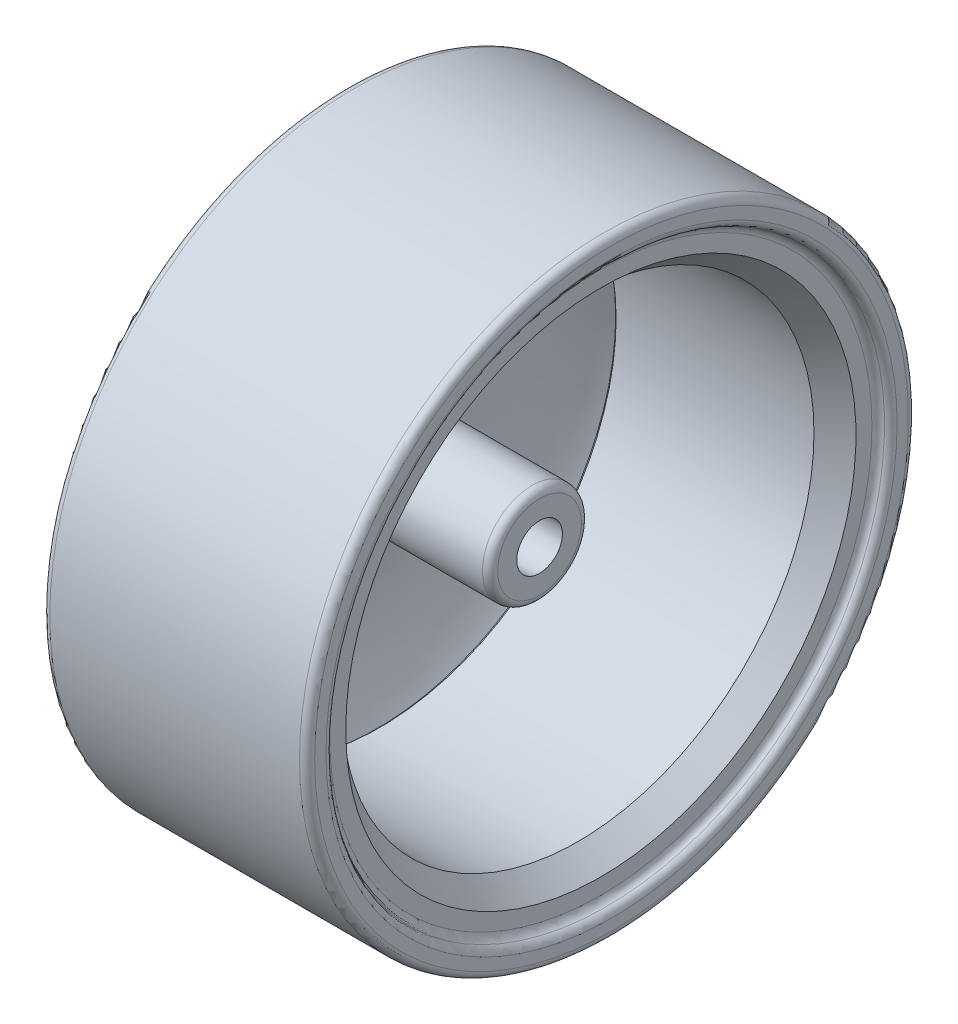
SolidWorks part; units mm, degrees
ref_plane "Front Plane" through (0, 0, 0) normal (0, 0, 1) x (1, 0, 0)
ref_plane "Top Plane" through (0, 0, 0) normal (0, 1, 0) x (1, 0, 0)
ref_plane "Right Plane" through (0, 0, 0) normal (1, 0, 0) x (0, 0, -1)
sketch "Sketch1" plane through (0, 0, 0) normal (0, 1, 0) x (1, 0, 0)
  line L0 (-5, 0) -> (5, 0) construction
  line L1 (0, 0) -> (0, 15.5) construction
  line L2 (6.5, 15.5) -> (-6.5, 15.5)
  line L3 (-6.5, 15.5) -> (-8, 16.7586)
  line L4 (-8, 16.7586) -> (-8, 18.2586)
  line L5 (-8, 18.2586) -> (-6.5, 18.2586)
  line L6 (-6.5, 18.2586) -> (-5, 16.5)
  line L7 (-5, 16.5) -> (5, 16.5)
  line L9 (6.5, 18.2586) -> (5, 16.5)
  line L10 (6.5, 15.5) -> (8, 16.7586)
  line L11 (8, 16.7586) -> (8, 18.2586)
  line L12 (8, 18.2586) -> (6.5, 18.2586)
  point P9 (0, 0)
  dimension "D1" = 6.5
  dimension "D2" = 140
  dimension "D3" = 10
  dimension "D4" = 3
  dimension "D5" = 1.5
  dimension "D6" = 1
  dimension "D7" = 15.5
revolve "Revolve1" add sketch "Sketch1" angle 360 about L0
sketch "Sketch4" plane through (0, 0, 0) normal (0, 1, 0) x (1, 0, 0)
  line L0 (-3.9721, 2.5) -> (3.9721, 2.5) construction
  line L1 (3.9721, 2.5) -> (3.9721, 3.25)
  line L2 (3.9721, 3.25) -> (-7.2779, 3.25)
  line L3 (-8.0279, 2.5) -> (-8.0279, 4.3511)
  line L4 (-8.0279, 2.5) -> (-6.5279, 2.5)
  line L5 (-6.5279, 2.5) -> (-6.5279, 0)
  line L6 (-6.5279, 0) -> (-5.7779, 0)
  line L7 (-5.7779, 0) -> (-5.7779, 2.5)
  line L8 (-5.7779, 2.5) -> (3.9721, 2.5)
  line L9 (-5, 0) -> (5, 0) construction
  line L10 (-7.2779, 3.25) -> (-7.2779, 4.3511)
  line L11 (-7.2411, 16.1218) -> (-6.6665, 15.6397)
  line L12 (-6.5, 15.5) -> (-8, 16.7586) construction
  arc A0 (-8.0279, 4.3511) -> (-7.2411, 16.1218) centre (5.5704, 9.3537) cw
  arc A1 (-7.2779, 4.3511) -> (-6.6665, 15.6397) centre (4.1456, 9.3933) cw
  point P2 (0, 2.5)
  dimension "D9" = 0.75
  dimension "D1" = 0.75
  dimension "D2" = 11.25
  dimension "D3" = 12
  dimension "D4" = 1.5
  dimension "D5" = 0.75
  dimension "D6" = 2.5
  dimension "D7" = 2.5
  dimension "D8" = 0.75
revolve "Revolve2" add sketch "Sketch4" angle 360 about L0
sketch "Sketch5" plane through (0, 0, 0) normal (1, 0, 0) x (0, 0, -1)
  line L0 (0, 0) -> (0, 15.1416) construction
  line L1 (6.3108, 13.7638) -> (1.5, 9.727)
  line L2 (-6.3108, 13.7638) -> (-1.5, 9.727)
  line L3 (15.0403, -1.7487) -> (9.7145, 1.5792)
  line L4 (11.14, 10.2552) -> (8.7874, 4.4324)
  line L5 (2.9846, -14.8446) -> (4.5039, -8.751)
  line L6 (13.1957, -7.4257) -> (6.9309, -6.9877)
  line L7 (-13.1957, -7.4257) -> (-6.9309, -6.9877)
  line L8 (-2.9846, -14.8446) -> (-4.5039, -8.751)
  line L9 (-11.14, 10.2552) -> (-8.7874, 4.4324)
  line L10 (-15.0403, -1.7487) -> (-9.7145, 1.5792)
  arc A0 (-13.1957, -7.4257) -> (-2.9846, -14.8446) centre (0, 0) ccw
  arc A1 (1.5, 9.727) -> (-1.5, 9.727) centre (0, 0) ccw
  arc A2 (9.7145, 1.5792) -> (8.7874, 4.4324) centre (0, 0) ccw
  arc A3 (-11.14, 10.2552) -> (-15.0403, -1.7487) centre (0, 0) ccw
  arc A4 (4.5039, -8.751) -> (6.9309, -6.9877) centre (0, 0) ccw
  arc A5 (-11.14, 10.2552) -> (-15.0403, -1.7487) centre (0, 0) ccw
  arc A6 (-6.9309, -6.9877) -> (-4.5039, -8.751) centre (0, 0) ccw
  arc A7 (-11.14, 10.2552) -> (-15.0403, -1.7487) centre (0, 0) ccw
  arc A8 (-8.7874, 4.4324) -> (-9.7145, 1.5792) centre (0, 0) ccw
  arc A9 (-11.14, 10.2552) -> (-15.0403, -1.7487) centre (0, 0) ccw
  arc A10 (-13.1957, -7.4257) -> (-2.9846, -14.8446) centre (0, 0) ccw
  arc A11 (-13.1957, -7.4257) -> (-2.9846, -14.8446) centre (0, 0) ccw
  arc A12 (-13.1957, -7.4257) -> (-2.9846, -14.8446) centre (0, 0) ccw
  arc A13 (-13.1957, -7.4257) -> (-2.9846, -14.8446) centre (0, 0) ccw
  arc A14 (2.9846, -14.8446) -> (13.1957, -7.4257) centre (0, 0) ccw
  arc A15 (2.9846, -14.8446) -> (13.1957, -7.4257) centre (0, 0) ccw
  arc A16 (2.9846, -14.8446) -> (13.1957, -7.4257) centre (0, 0) ccw
  arc A17 (2.9846, -14.8446) -> (13.1957, -7.4257) centre (0, 0) ccw
  arc A18 (2.9846, -14.8446) -> (13.1957, -7.4257) centre (0, 0) ccw
  arc A19 (15.0403, -1.7487) -> (11.14, 10.2552) centre (0, 0) ccw
  arc A20 (15.0403, -1.7487) -> (11.14, 10.2552) centre (0, 0) ccw
  arc A21 (15.0403, -1.7487) -> (11.14, 10.2552) centre (0, 0) ccw
  arc A22 (15.0403, -1.7487) -> (11.14, 10.2552) centre (0, 0) ccw
  arc A23 (15.0403, -1.7487) -> (11.14, 10.2552) centre (0, 0) ccw
  arc A24 (6.3108, 13.7638) -> (-6.3108, 13.7638) centre (0, 0) ccw
  arc A25 (6.3108, 13.7638) -> (-6.3108, 13.7638) centre (0, 0) ccw
  arc A26 (6.3108, 13.7638) -> (-6.3108, 13.7638) centre (0, 0) ccw
  arc A27 (6.3108, 13.7638) -> (-6.3108, 13.7638) centre (0, 0) ccw
  arc A28 (6.3108, 13.7638) -> (-6.3108, 13.7638) centre (0, 0) ccw
  point P30 (0, 0)
  dimension "D1" = 50
  dimension "D2" = 3
  dimension "D3" = 5
sketch "Sketch6" plane through (0, 0, 0) normal (0, 0, 1) x (1, 0, 0)
  line L0 (-5, 16.5) -> (5, 16.5)
  line L1 (5, 16.5) -> (-5, 16.5) construction
  line L2 (5, 16.5) -> (6.5, 18.2586)
  line L3 (-5, 16.5) -> (-6.5, 18.2586)
  line L4 (-6.5, 18.2586) -> (-8.2, 18.2586)
  line L5 (-8.7, 18.7586) -> (-8.7, 19.5)
  line L6 (-8.2, 20) -> (8.2, 20)
  line L7 (8.7, 19.5) -> (8.7, 18.7586)
  line L8 (8.2, 18.2586) -> (6.5, 18.2586)
  line L9 (-6.5, 18.2586) -> (-6.5, -18.2586) construction
  line L10 (6.5, 18.2586) -> (6.5, -18.2586) construction
  line L11 (-5, 0) -> (5, 0) construction
  arc A0 (-8.2, 20) -> (-8.7, 19.5) centre (-8.2, 19.5) ccw
  arc A1 (-8.7, 18.7586) -> (-8.2, 18.2586) centre (-8.2, 18.7586) ccw
  arc A2 (8.2, 20) -> (8.7, 19.5) centre (8.2, 19.5) cw
  arc A3 (8.7, 18.7586) -> (8.2, 18.2586) centre (8.2, 18.7586) cw
  point P23 (-8.7, 18.2586)
  point P26 (8.7, 20)
  point P29 (8.7, 18.2586)
  dimension "D4" = 0.5
  dimension "D1" = 2.2
  dimension "D2" = 2.2
  dimension "D3" = 20
revolve "Revolve3" add sketch "Sketch6" angle 360 about L0
fillet "Fillet2" radius 0.5 3 edges at (-8.0279, 0, 4.3511) (-8.0279, 0, 2.5) (-6.5279, 0, 2.5)
fillet "Fillet3" radius 0.5 2 edges at (8, 0, 18.2586) (-8, 0, -18.2586)
sketch "Sketch7" plane through (3.9721, 0, 0) normal (1, 0, 0) x (0, 0, -1)
  circle A0 centre (0, 0) radius 2.5
  circle A1 centre (0, 0) radius 1.5
  dimension "D1" = 3
extrude "Boss-Extrude1" add sketch "Sketch7" against normal blind 10
fillet "Fillet4" radius 0.5 1 edges at (3.9721, 0, 3.25)
